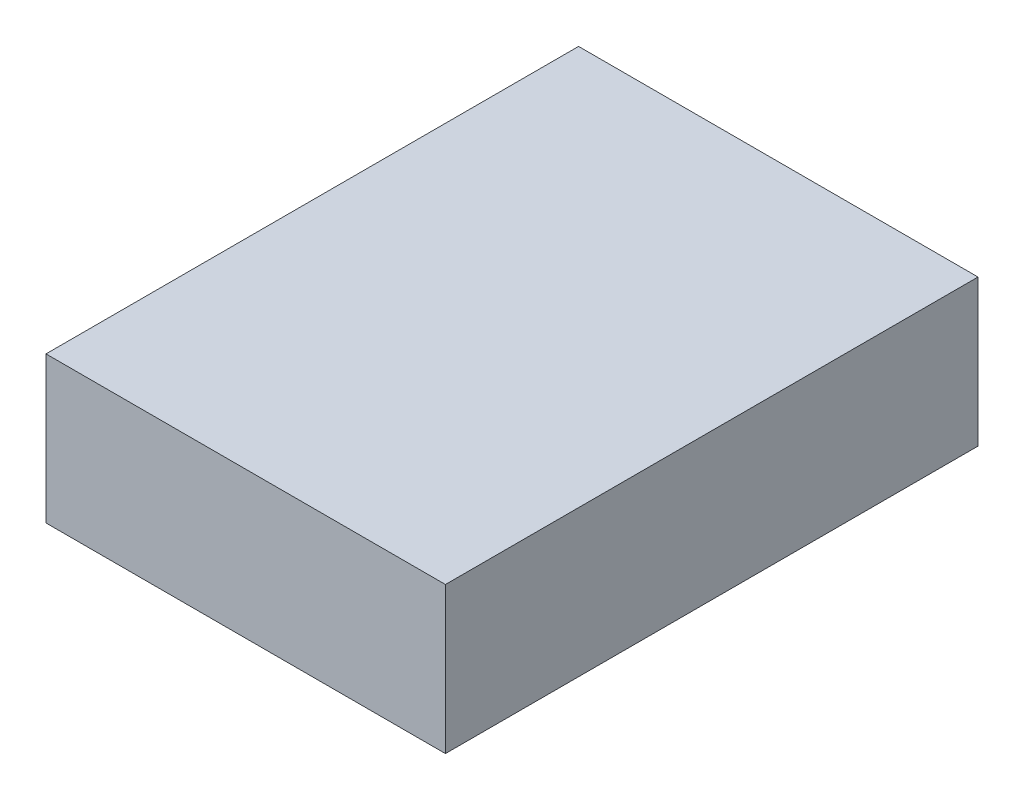
SolidWorks part; units mm, degrees
ref_plane "前视基准面" through (0, 0, 0) normal (0, 0, 1) x (1, 0, 0)
ref_plane "上视基准面" through (0, 0, 0) normal (0, 1, 0) x (1, 0, 0)
ref_plane "右视基准面" through (0, 0, 0) normal (1, 0, 0) x (0, 0, -1)
sketch "草图1" plane through (0, 0, 0) normal (0, 1, 0) x (1, 0, 0)
  line L1 (0, 0) -> (60, 0)
  line L2 (0, 0) -> (0, -80)
  line L3 (0, -80) -> (60, -80)
  line L4 (60, 0) -> (60, -80)
  dimension "D1" = 80
  dimension "D2" = 60
extrude "凸台-拉伸1" add sketch "草图1" along normal blind 22
